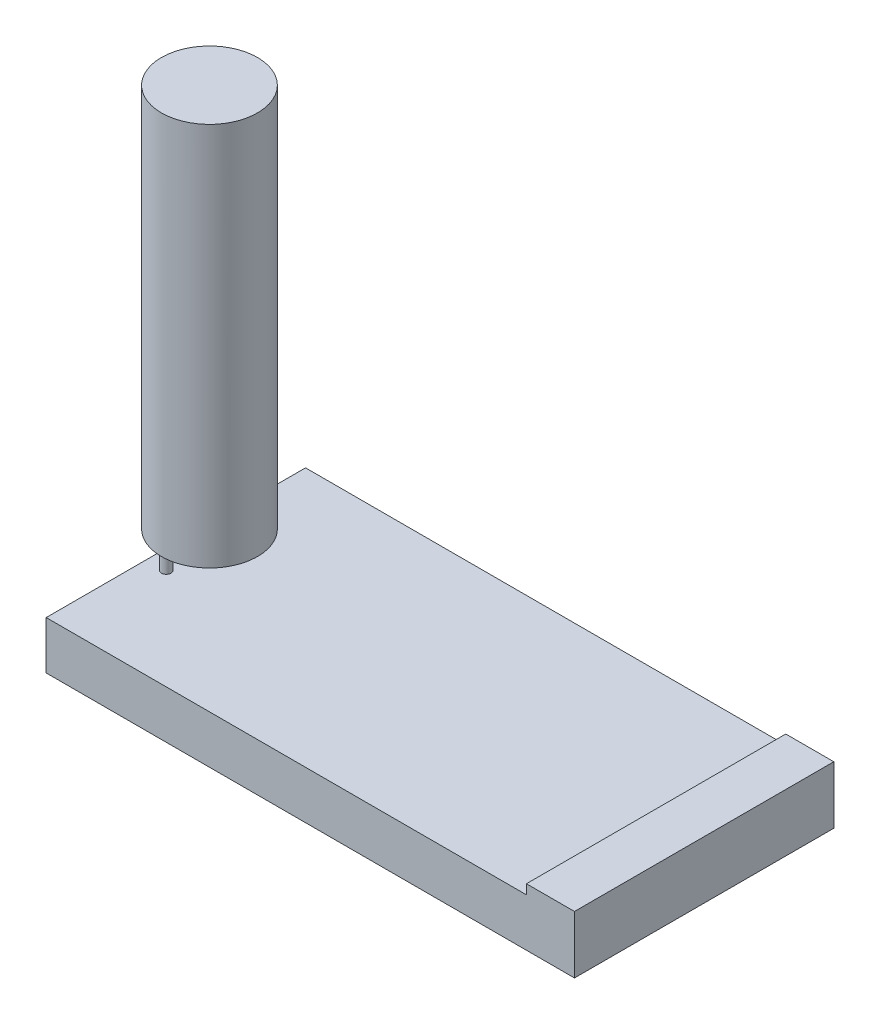
SolidWorks part; units mm, degrees
ref_plane "Спереди" through (0, 0, 0) normal (0, 0, 1) x (1, 0, 0)
ref_plane "Сверху" through (0, 0, 0) normal (0, 1, 0) x (1, 0, 0)
ref_plane "Справа" through (0, 0, 0) normal (1, 0, 0) x (0, 0, -1)
other "Configuration Table"
sketch "Эскиз1" plane through (0, 0, 0) normal (0, 1, 0) x (1, 0, 0)
  line L1 (-13.75, -6.75) -> (13.75, -6.75)
  line L2 (-13.75, -6.75) -> (-13.75, 6.75)
  line L3 (-13.75, 6.75) -> (13.75, 6.75)
  line L4 (13.75, -6.75) -> (13.75, 6.75)
  line L5 (-13.75, -6.75) -> (13.75, 6.75) construction
  line L6 (-13.75, 6.75) -> (13.75, -6.75) construction
  point P0 (0, 0)
  dimension "D1" = 13.5
  dimension "D2" = 27.5
extrude "Бобышка-Вытянуть1" add sketch "Эскиз1" along normal blind 2.5
sketch "Эскиз2" plane through (0, 0, 0) normal (0, -1, 0) x (1, 0, 0)
  line L1 (13.75, 6.75) -> (11.25, 6.75)
  line L2 (13.75, 6.75) -> (13.75, -6.75)
  line L3 (13.75, -6.75) -> (11.25, -6.75)
  line L4 (13.75, -6.75) -> (13.75, 6.75)
  line L5 (13.75, 6.75) -> (-13.75, 6.75)
  line L6 (-13.75, 6.75) -> (-13.75, -6.75)
  line L7 (-13.75, -6.75) -> (13.75, -6.75)
  line L8 (13.75, -6.75) -> (13.75, 6.75)
  line L9 (13.75, 6.75) -> (-13.75, 6.75)
  line L10 (-13.75, 6.75) -> (-13.75, -6.75)
  line L11 (-13.75, -6.75) -> (13.75, -6.75)
  line L12 (11.25, 6.75) -> (11.25, -6.75)
  line M9 (13.75, -6.75) -> (13.75, 6.75)
  line M10 (13.75, 6.75) -> (-13.75, 6.75)
  line M12 (-13.75, -6.75) -> (13.75, -6.75)
  dimension "D2" = 2.5
  dimension "D1" = 0
extrude "Бобышка-Вытянуть2" add sketch "Эскиз2" against normal blind 3 contours L12 M10 M12 M9
sketch "Эскиз3" plane through (-13.75, 0, 0) normal (-1, 0, 0) x (0, 0, 1)
  line L0 (-6.75, 0) -> (6.75, 0) construction
  line L1 (6.75, 2.5) -> (6.75, 0) construction
  circle A0 centre (1.75, 1.25) radius 0.25
  dimension "D1" = 0.5
  dimension "D2" = 1.25
  dimension "D3" = 5
sketch "Эскиз5" plane through (0, 2.5, 0) normal (0, 1, 0) x (1, 0, 0)
  line L2 (-13.75, 6.75) -> (-13.75, -6.75) construction
  circle A0 centre (-12.75, -1.5) radius 0.25
  dimension "D1" = 0.5
  dimension "D2" = 1.5
  dimension "D3" = 1
extrude "Бобышка-Вытянуть6" add sketch "Эскиз5" along normal blind 3
sketch "Эскиз6" plane through (0, 5.5, 0) normal (0, 1, 0) x (1, 0, 0)
  line L0 (-1012.75, -1.5) -> (48987.25, -1.5) construction
  circle A0 centre (-10.5, -1.5) radius 2.5
  circle A1 centre (-12.75, -1.5) radius 0.25 construction
  dimension "D1" = 5
extrude "Бобышка-Вытянуть7" add sketch "Эскиз6" along normal blind 20
